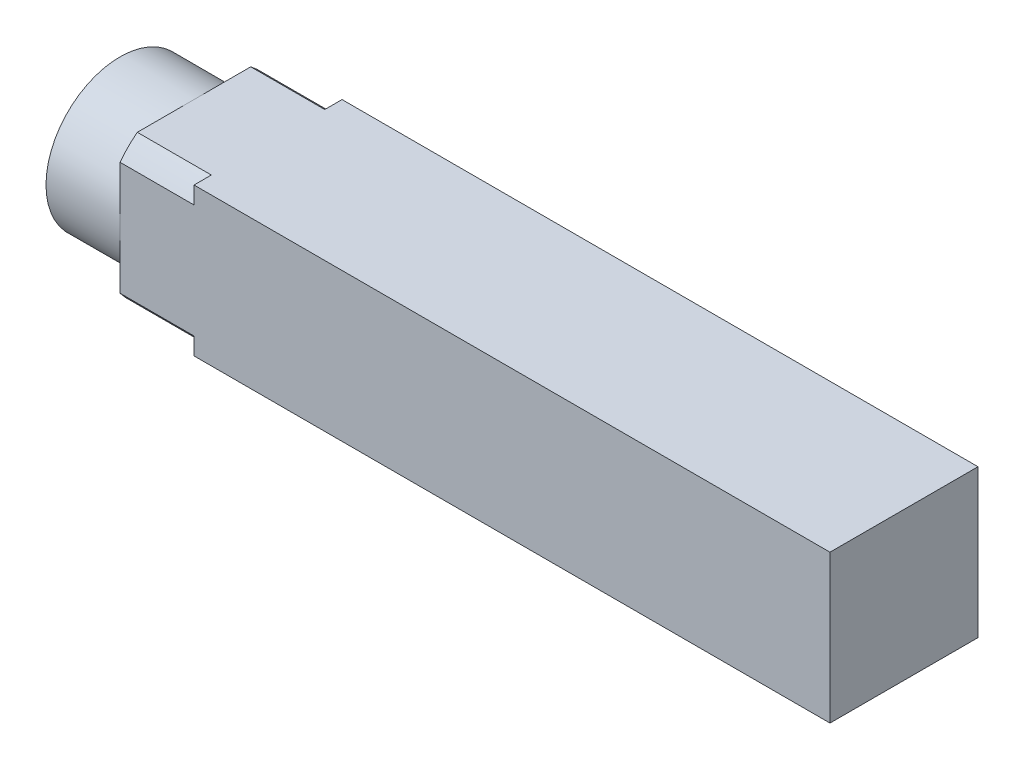
SolidWorks part; units mm, degrees
ref_plane "Front Plane" through (0, 0, 0) normal (0, 0, 1) x (1, 0, 0)
ref_plane "Top Plane" through (0, 0, 0) normal (0, 1, 0) x (1, 0, 0)
ref_plane "Right Plane" through (0, 0, 0) normal (1, 0, 0) x (0, 0, -1)
sketch "Sketch1" plane through (0, 0, 0) normal (1, 0, 0) x (0, 0, -1)
  line L1 (-3.175, -3.175) -> (3.175, -3.175)
  line L2 (-3.175, -3.175) -> (-3.175, 3.175)
  line L3 (-3.175, 3.175) -> (3.175, 3.175)
  line L4 (3.175, -3.175) -> (3.175, 3.175)
  line L5 (-3.175, -3.175) -> (3.175, 3.175) construction
  line L6 (-3.175, 3.175) -> (3.175, -3.175) construction
  point P0 (0, 0)
  dimension "D1" = 6.35
extrude "Boss-Extrude1" add sketch "Sketch1" along normal blind 33.6321
sketch "Sketch3" plane through (0, 0, 0) normal (-1, 0, 0) x (0, 0, 1)
  line L1 (-3.175, 3.175) -> (3.175, 3.175) construction
  line L3 (4.7625, -4.7625) -> (-4.7625, -4.7625)
  line L4 (4.7625, -4.7625) -> (4.7625, 4.7625)
  line L5 (4.7625, 4.7625) -> (-4.7625, 4.7625)
  line L6 (-4.7625, -4.7625) -> (-4.7625, 4.7625)
  line L7 (4.7625, -4.7625) -> (-4.7625, 4.7625) construction
  line L8 (4.7625, 4.7625) -> (-4.7625, -4.7625) construction
  circle A0 centre (0, 0) radius 3.175
  dimension "D1" = 9.525
extrude "Cut-Extrude2" cut sketch "Sketch3" against normal blind 3.175
sketch "Sketch4" plane through (3.175, 0, 0) normal (1, 0, 0) x (0, 0, -1)
  line L1 (3.9688, -3.9688) -> (-3.9687, -3.9688)
  line L2 (3.9688, -3.9688) -> (3.9688, 3.9687)
  line L3 (3.9688, 3.9687) -> (-3.9687, 3.9687)
  line L4 (3.175, -3.175) -> (3.175, 3.175)
  line L5 (3.175, 3.175) -> (-3.175, 3.175)
  line L6 (-3.175, 3.175) -> (-3.175, -3.175)
  line L7 (-3.175, -3.175) -> (3.175, -3.175)
  line L8 (3.175, -2.433) -> (3.175, 2.433)
  line L9 (2.433, 3.175) -> (-2.433, 3.175)
  line L10 (-3.175, 2.433) -> (-3.175, -2.433)
  line L11 (-2.433, -3.175) -> (2.433, -3.175)
  line L12 (-3.9687, -3.9688) -> (-3.9687, 3.9687)
  line L13 (3.9688, -3.9688) -> (-3.9687, 3.9687) construction
  line L14 (3.9688, 3.9687) -> (-3.9687, -3.9688) construction
  arc A0 (-3.175, -2.433) -> (-2.433, -3.175) centre (0, 0) ccw
  arc A1 (2.433, -3.175) -> (3.175, -2.433) centre (0, 0) ccw
  arc A2 (3.175, 2.433) -> (2.433, 3.175) centre (0, 0) ccw
  arc A3 (-2.433, 3.175) -> (-3.175, 2.433) centre (0, 0) ccw
  dimension "D1" = 8
  dimension "D3" = 7.9375
  dimension "D2" = 0
extrude "Cut-Extrude3" cut sketch "Sketch4" along normal blind 3.175
